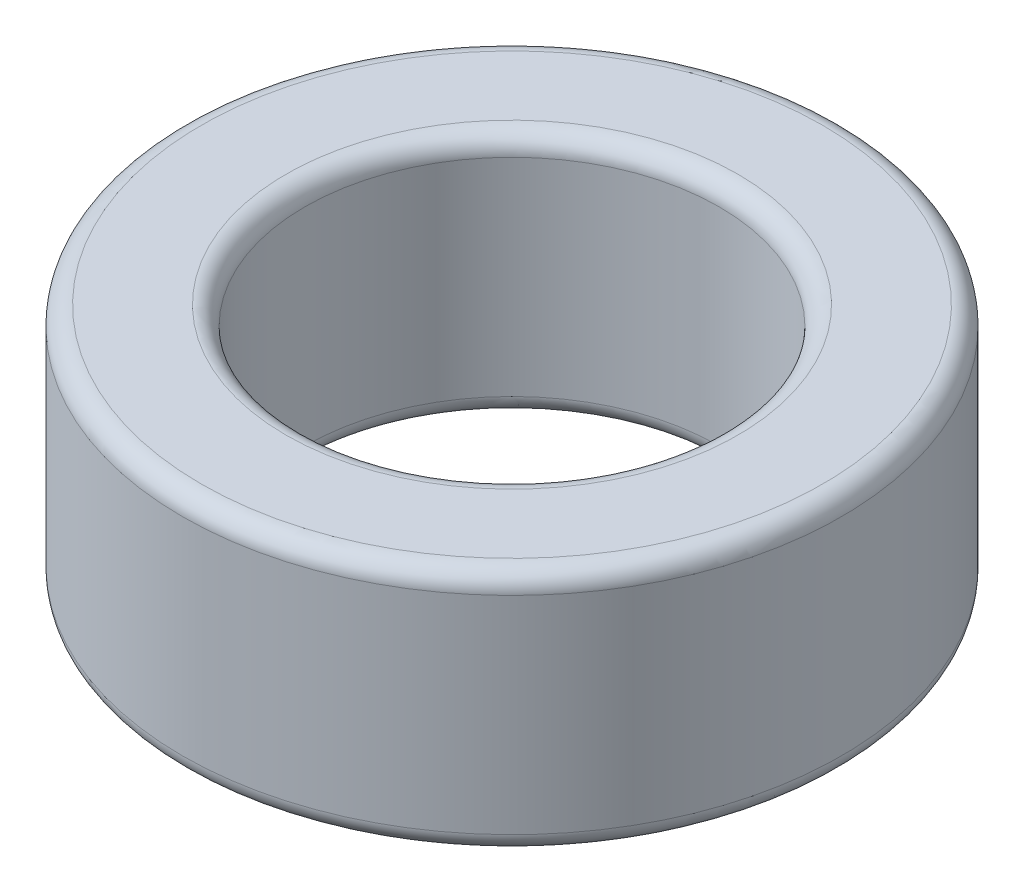
SolidWorks part; units mm, degrees
ref_plane "Front Plane" through (0, 0, 0) normal (0, 0, 1) x (1, 0, 0)
ref_plane "Top Plane" through (0, 0, 0) normal (0, 1, 0) x (1, 0, 0)
ref_plane "Right Plane" through (0, 0, 0) normal (1, 0, 0) x (0, 0, -1)
sketch "Sketch1" plane through (0, 0, 0) normal (0, 1, 0) x (1, 0, 0)
  circle A0 centre (0, 0) radius 17.5
  circle A1 centre (0, 0) radius 11
  dimension "D1" = 35
  dimension "D2" = 22
extrude "Boss-Extrude1" add sketch "Sketch1" along normal blind 13
fillet "Fillet1" radius 1 4 edges at (0, 0, 11) (0, 0, 17.5) (0, 13, 11) (0, 13, 17.5)
